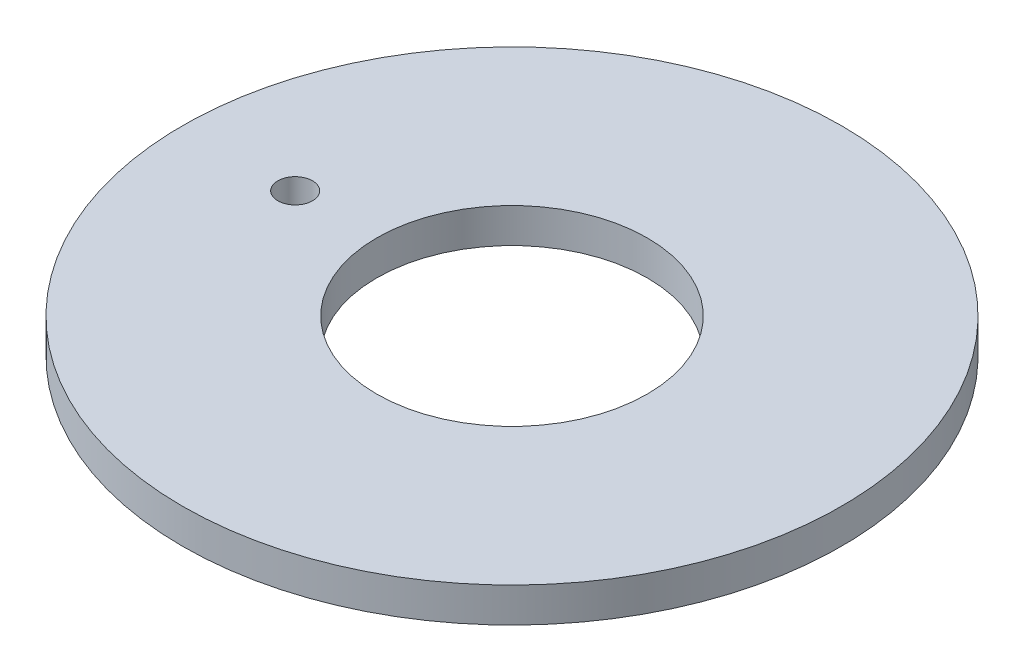
SolidWorks part; units mm, degrees
ref_plane "Front Plane" through (0, 0, 0) normal (0, 0, 1) x (1, 0, 0)
ref_plane "Top Plane" through (0, 0, 0) normal (0, 1, 0) x (1, 0, 0)
ref_plane "Right Plane" through (0, 0, 0) normal (1, 0, 0) x (0, 0, -1)
sketch "Sketch1" plane through (0, 0, 0) normal (0, 1, 0) x (1, 0, 0)
  circle A0 centre (0, 0) radius 38
  circle A1 centre (0, 0) radius 15.6
  dimension "D1" = 31.2
  dimension "D2" = 76
extrude "Boss-Extrude1" add sketch "Sketch1" along normal blind 4
sketch "Sketch2" plane through (0, 4, 0) normal (0, 1, 0) x (1, 0, 0)
  circle A0 centre (0, 0) radius 25 construction
  circle A1 centre (-25, 0) radius 2
  circle A2 centre (0, 0) radius 15.6 construction
  circle A3 centre (0, 0) radius 38 construction
  point P5 (-27, 0)
  point P6 (-23, 0)
  point P7 (-15.6, 0)
  point P8 (-38, 0)
  dimension "D1" = 50
  dimension "D2" = 4
extrude "Cut-Extrude1" cut sketch "Sketch2" against normal through all
